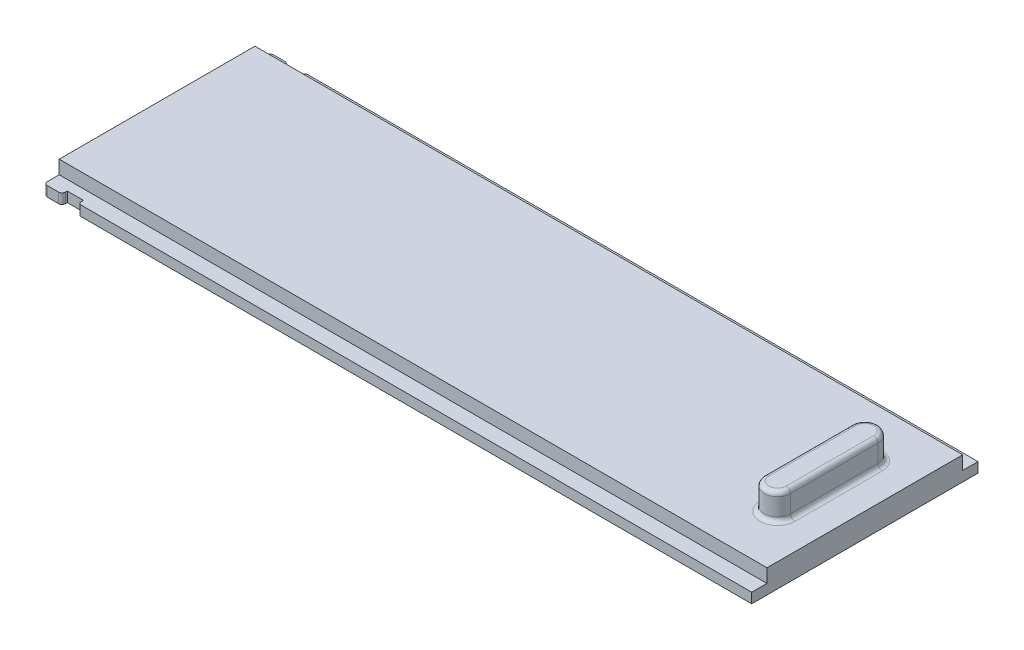
SolidWorks part; units mm, degrees
ref_plane "Front Plane" through (0, 0, 0) normal (0, 0, 1) x (1, 0, 0)
ref_plane "Top Plane" through (0, 0, 0) normal (0, 1, 0) x (1, 0, 0)
ref_plane "Right Plane" through (0, 0, 0) normal (1, 0, 0) x (0, 0, -1)
sketch "Sketch1" plane through (0, 0, 0) normal (0, 1, 0) x (1, 0, 0)
  line L1 (0, 0) -> (81, 0)
  line L2 (0, 0) -> (0, 29)
  line L3 (0, 29) -> (81, 29)
  line L4 (81, 0) -> (81, 29)
  dimension "D1" = 29
  dimension "D2" = 81
extrude "Boss-Extrude1" add sketch "Sketch1" along normal blind 3
sketch "Sketch2" plane through (81, 0, 0) normal (1, 0, 0) x (0, 0, -1)
  line L0 (0, 0) -> (29, 0) construction
  line L1 (0, 3) -> (3, 3)
  line L2 (0, 3) -> (0, 0)
  line L3 (0, 0) -> (1.25, 0)
  line L4 (3, 3) -> (3, 1.75)
  line L5 (3, 1.75) -> (1.25, 1.75)
  line L6 (1.25, 1.75) -> (1.25, 0)
  line L11 (14.5, 3) -> (14.5, 0) construction
  line L12 (0, 3) -> (29, 3) construction
  line L21 (29, 0) -> (27.75, 0)
  line L22 (29, 3) -> (26, 3)
  line L25 (27.75, 1.75) -> (26, 1.75)
  line L26 (26, 1.75) -> (26, 3)
  line L31 (27.75, 1.75) -> (27.75, 0)
  line L35 (29, 3) -> (29, 0)
  dimension "D1" = 1.25
  dimension "D2" = 1.25
  dimension "D3" = 3
extrude "Cut-Extrude2" cut sketch "Sketch2" against normal up to surface (81 mm away) up to face at (0, 1.5, -14.5)
sketch "Sketch4" plane through (81, 0, 0) normal (1, 0, 0) x (0, 0, -1)
  line L6 (27.75, 0) -> (27.45, 0)
  line L8 (27.75, 1.75) -> (27.75, 0)
  line L17 (14.5, 3) -> (14.5, 0) construction
  line L18 (3, 3) -> (26, 3) construction
  line L19 (1.25, 0) -> (27.75, 0) construction
  line L32 (25.7, 1.45) -> (25.7, 3)
  line L33 (27.45, 1.45) -> (25.7, 1.45)
  line L34 (27.45, 0) -> (27.45, 1.45)
  line L35 (26, 1.75) -> (27.75, 1.75)
  line L36 (26, 3) -> (26, 1.75)
  line L37 (25.7, 3) -> (26, 3)
  line L44 (3.3, 3) -> (3, 3)
  line L45 (3, 3) -> (3, 1.75)
  line L46 (3, 1.75) -> (1.25, 1.75)
  line L47 (1.55, 0) -> (1.55, 1.45)
  line L48 (1.55, 1.45) -> (3.3, 1.45)
  line L49 (3.3, 1.45) -> (3.3, 3)
  line L50 (1.55, 0) -> (1.55, 1.45)
  line L51 (1.55, 1.45) -> (3.3, 1.45)
  line L52 (3.3, 1.45) -> (3.3, 3)
  line L53 (1.25, 1.75) -> (1.25, 0)
  line L54 (1.25, 0) -> (1.55, 0)
  dimension "D1" = 0.3
extrude "Cut-Extrude3" cut sketch "Sketch4" against normal up to surface (81 mm away) up to face at (0, 1.625, -14.5)
sketch "Sketch6" plane through (0, 0, -1.55) normal (0, 0, 1) x (1, 0, 0)
  line L0 (0, 0.675) -> (3, 0.675) construction
  line L3 (2.075, -0.1) -> (3.925, -0.1)
  line L4 (2.075, -0.1) -> (2.075, 1.45)
  line L5 (2.075, 1.45) -> (3.925, 1.45)
  line L6 (3.925, -0.1) -> (3.925, 1.45)
  line L7 (2.075, -0.1) -> (3.925, 1.45) construction
  line L8 (2.075, 1.45) -> (3.925, -0.1) construction
  line L11 (0, 1.45) -> (81, 1.45) construction
  line L12 (0, 1.45) -> (0, 0) construction
  dimension "D1" = 3
  dimension "D3" = 1.85
  dimension "D4" = 0.775
extrude "Cut-Extrude5" cut sketch "Sketch6" against normal blind 0.6
fillet "Fillet6" radius 0.4 1 edges at (2.075, 0.725, -1.55)
chamfer "Chamfer2" distance 0.2 angle 45 1 edges at (3.925, 0.725, -1.55)
sketch "Sketch7" plane through (0, 0, -27.45) normal (0, 0, -1) x (-1, 0, 0)
  line L0 (-3, 0.675) -> (0, 0.675) construction
  line L3 (-2.075, 1.45) -> (-3.925, 1.45)
  line L4 (-2.075, 1.45) -> (-2.075, -0.1)
  line L5 (-2.075, -0.1) -> (-3.925, -0.1)
  line L6 (-3.925, 1.45) -> (-3.925, -0.1)
  line L7 (-2.075, 1.45) -> (-3.925, -0.1) construction
  line L8 (-2.075, -0.1) -> (-3.925, 1.45) construction
  line L9 (0, 1.45) -> (-81, 1.45) construction
  line L10 (0, 0) -> (0, 1.45) construction
  dimension "D1" = 3
  dimension "D3" = 1.85
  dimension "D4" = 0.775
extrude "Cut-Extrude6" cut sketch "Sketch7" against normal blind 0.6
fillet "Fillet7" radius 0.4 1 edges at (2.075, 0.725, -27.45)
chamfer "Chamfer3" distance 0.2 angle 45 1 edges at (3.925, 0.725, -27.45)
sketch "Sketch9" plane through (0, 3, 0) normal (0, 1, 0) x (1, 0, 0)
  line L0 (76, 9.5) -> (76, 19.5) construction
  line L1 (74.5, 9.5) -> (74.5, 19.5)
  line L2 (77.5, 9.5) -> (77.5, 19.5)
  line L3 (76, 8) -> (76, 3.3) construction
  line L5 (0, 3.3) -> (81, 3.3) construction
  line L14 (76, 21) -> (76, 25.7) construction
  line L15 (0, 25.7) -> (81, 25.7) construction
  line L16 (81, 3.3) -> (81, 25.7) construction
  arc A0 (74.5, 9.5) -> (77.5, 9.5) centre (76, 9.5) ccw
  arc A1 (77.5, 19.5) -> (74.5, 19.5) centre (76, 19.5) ccw
  point P2 (76, 14.5)
  dimension "D1" = 3
  dimension "D2" = 10
  dimension "D3" = 5
sketch "Sketch11" plane through (0, 0, 0) normal (0, -1, 0) x (-1, 0, 0)
  line L1 (0, 27.45) -> (-81, 27.45)
  line L2 (0, 27.45) -> (0, 1.55)
  line L3 (0, 1.55) -> (-81, 1.55)
  line L4 (-81, 27.45) -> (-81, 1.55)
extrude "Cut-Extrude7" cut sketch "Sketch11" against normal blind 0.2
fillet "Fillet8" radius 0.4 2 edges at (0, 0.825, -27.45) (0, 0.825, -1.55)
extrude "Boss-Extrude2" add sketch "Sketch9" along normal blind 3
fillet "Fillet11" radius 0.5 8 edges at (74.5, 3, -14.5) (76, 3, -21) (77.5, 3, -14.5) (76, 3, -8) (76, 6, -8) (74.5, 6, -14.5) (76, 6, -21) (77.5, 6, -14.5)
sketch "Sketch12" plane through (81, 0, 0) normal (1, 0, 0) x (0, 0, -1)
  line L0 (27.45, 1.45) -> (27.45, 0.2) construction
  line L1 (1.55, 0.2) -> (27.45, 0.2)
  line L2 (1.55, 0.2) -> (1.55, 0.3)
  line L3 (1.55, 0.3) -> (27.45, 0.3)
  line L4 (27.45, 0.2) -> (27.45, 0.3)
  dimension "D1" = 0.1
extrude "Cut-Extrude8" cut sketch "Sketch12" against normal up to surface (81 mm away) up to face at (0, 1.525, -14.5)
